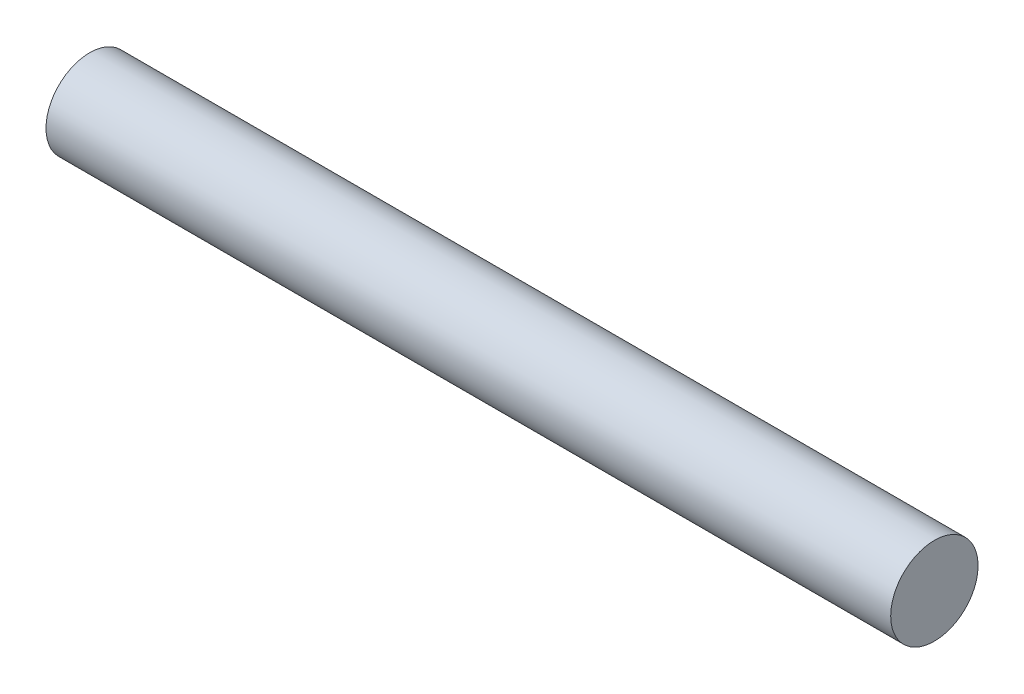
SolidWorks part; units mm, degrees
ref_plane "Front Plane" through (0, 0, 0) normal (0, 0, 1) x (1, 0, 0)
ref_plane "Top Plane" through (0, 0, 0) normal (0, 1, 0) x (1, 0, 0)
ref_plane "Right Plane" through (0, 0, 0) normal (1, 0, 0) x (0, 0, -1)
sketch "Sketch1" plane through (0, 0, 0) normal (1, 0, 0) x (0, 0, -1)
  circle A0 centre (0, 0) radius 6
  dimension "D1" = 12
extrude "Boss-Extrude1" add sketch "Sketch1" along normal blind 116
